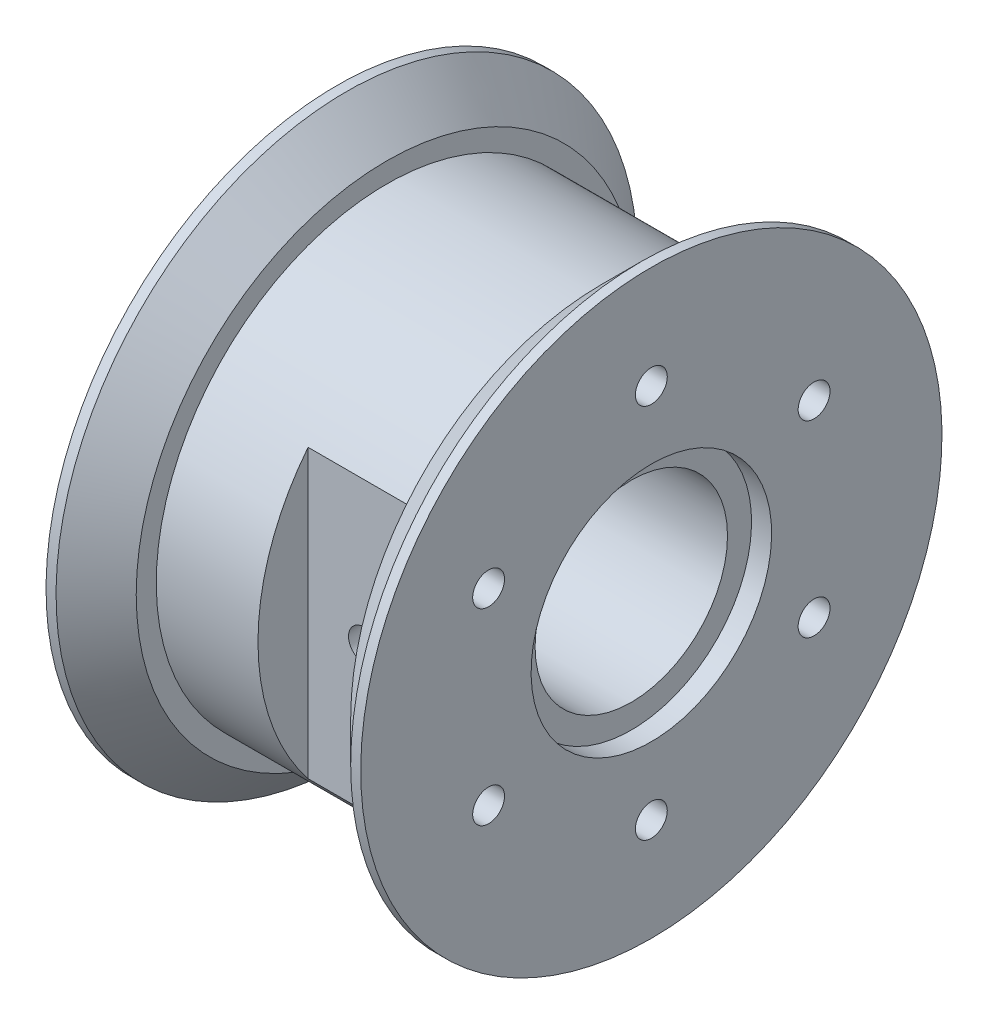
SolidWorks part; units mm, degrees
material "1060 Alloy"
ref_plane "Front Plane" through (0, 0, 0) normal (0, 0, 1) x (1, 0, 0)
ref_plane "Top Plane" through (0, 0, 0) normal (0, 1, 0) x (1, 0, 0)
ref_plane "Right Plane" through (0, 0, 0) normal (1, 0, 0) x (0, 0, -1)
sketch "Sketch3" plane through (0, 0, 0) normal (0, 0, 1) x (1, 0, 0)
  line L0 (-36.3274, 0) -> (36.3274, 0) construction
  line L1 (-19.939, 12.192) -> (19.939, 12.192)
  line L2 (19.939, 12.192) -> (19.939, 36.83)
  line L3 (19.939, 36.83) -> (13.589, 36.83)
  line L4 (13.589, 36.83) -> (13.589, 29.21)
  line L5 (13.589, 29.21) -> (-13.589, 29.21)
  line L6 (-13.589, 29.21) -> (-13.589, 36.83)
  line L7 (-13.589, 36.83) -> (-19.939, 36.83)
  line L8 (-19.939, 36.83) -> (-19.939, 12.192)
  point P4 (0, 12.192)
  point P12 (0, 0)
  dimension "D1" = 39.878
  dimension "D2" = 58.42
  dimension "D3" = 6.35
  dimension "D4" = 7.62
  dimension "D5" = 24.384
revolve "Revolve1" add sketch "Sketch3" angle 360 about L0
sketch "Sketch4" plane through (19.939, 0, 0) normal (1, 0, 0) x (0, 0, -1)
  circle A0 centre (0, 0) radius 15.24
  dimension "D1" = 30.48
extrude "Cut-Extrude1" cut sketch "Sketch4" against normal blind 2.54
mirror "Mirror1" about plane through (0, 0, 0) normal (1, 0, 0) of "Cut-Extrude1"
hole_wizard "#10-32 Tapped Hole1" positions "Sketch5" profile "Sketch7" tap size "#10-32" standard "ANSI Inch"
sketch "Sketch5" plane through (19.939, 0, 0) normal (1, 0, 0) x (0, 0, -1)
  circle A0 centre (0, 0) radius 23.8125 construction
  point P0 (0, -23.8125)
  dimension "D1" = 47.625
sketch "Sketch7" plane through (19.939, -23.8125, 0) normal (0, 1, 0) x (0, 0, -1)
  line L0 (0, 0) -> (0, 13.1513)
  line L1 (0, 13.1513) -> (2.0193, 11.938)
  line L2 (2.0193, 11.938) -> (2.0193, 0)
  line L5 (2.0193, 0) -> (0, 0)
  line L10 (0, 13.1513) -> (-2.0193, 11.938) construction
  line L11 (0, -6.35) -> (0, 107.95) construction
  dimension "Tap Drill Dia." = 4.0386
  dimension "Tap Drill Depth" = 11.938
  dimension "Drill Angle" = 118
cosmetic thread "Hole Thread1" parameters "D1"=9.652, "D2"=4.826
pattern_circular "CirPattern1" count 6 over 360 about axis through (0, 0, 0) along (1, 0, 0) of "#10-32 Tapped Hole1"
mirror "Mirror2" about plane through (0, 0, 0) normal (1, 0, 0) of "CirPattern1", "#10-32 Tapped Hole1"
sketch "Sketch9" plane through (0, 0, 0) normal (0, 1, 0) x (1, 0, 0)
  line L1 (13.589, -29.21) -> (-0.6985, -29.21)
  line L2 (13.589, -29.21) -> (13.589, -22.86)
  line L3 (13.589, -22.86) -> (-0.6985, -22.86)
  line L4 (-0.6985, -29.21) -> (-0.6985, -22.86)
  dimension "D1" = 6.35
  dimension "D2" = 14.2875
extrude "Cut-Extrude3" cut sketch "Sketch9" against normal through all both and the other way through all
hole_wizard "#10-32 Tapped Hole2" positions "Sketch10" profile "Sketch11" tap size "#10-32" standard "ANSI Inch"
sketch "Sketch10" plane through (0, 0, 22.86) normal (0, 0, 1) x (1, 0, 0)
  line L0 (-0.6985, -18.1836) -> (-0.6985, 18.1836) construction
  line L1 (21.9329, 0) -> (-21.9329, 0) construction
  point P0 (6.4452, 0)
  dimension "D1" = 7.1437
sketch "Sketch11" plane through (6.4453, 0, 22.86) normal (1, 0, 0) x (0, -1, 0)
  line L0 (0, 0) -> (0, 13.1513)
  line L1 (0, 13.1513) -> (2.0193, 11.938)
  line L2 (2.0193, 11.938) -> (2.0193, 0)
  line L5 (2.0193, 0) -> (0, 0)
  line L10 (0, 13.1513) -> (-2.0193, 11.938) construction
  line L11 (0, -6.35) -> (0, 107.95) construction
  dimension "Tap Drill Dia." = 4.0386
  dimension "Tap Drill Depth" = 11.938
  dimension "Drill Angle" = 118
cosmetic thread "Hole Thread2" parameters "D1"=9.652, "D2"=4.826
chamfer "Chamfer1" distance 5.08 angle 45 2 edges at (13.589, -36.83, 0) (-13.589, -36.83, 0)
